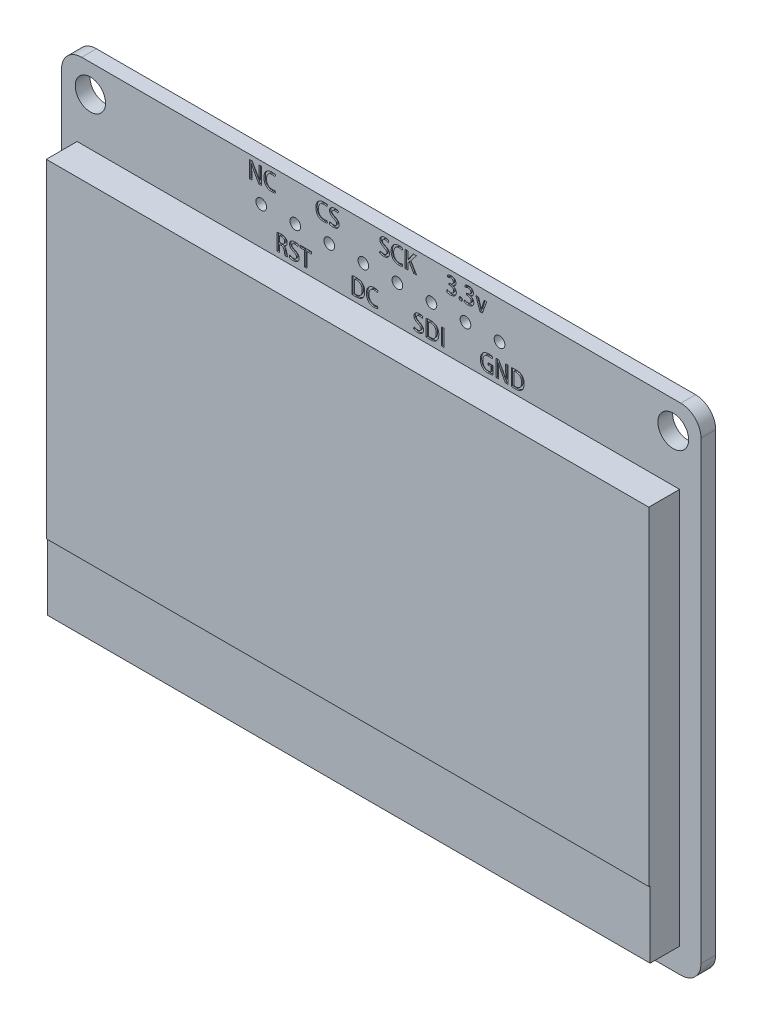
SolidWorks part; units mm, degrees
material "Plastique personnalisé"
ref_plane "Plan de face" through (0, 0, 0) normal (0, 0, 1) x (1, 0, 0)
ref_plane "Plan de dessus" through (0, 0, 0) normal (0, 1, 0) x (1, 0, 0)
ref_plane "Plan de droite" through (0, 0, 0) normal (1, 0, 0) x (0, 0, -1)
sketch "Esquisse1" plane through (0, 0, 0) normal (0, 0, 1) x (1, 0, 0)
  line L0 (4.6185, 246.0736) -> (52.2185, 246.0407) construction
  line L1 (40.983, 251.6357) -> (-0.5951, 251.6357) construction
  line L2 (4.5636, 236.0453) -> (4.5636, 254.0238) construction
  line L3 (29.8632, 214.6715) -> (54.4236, 214.6715) construction
  line L4 (52.2699, 246.817) -> (52.2699, 211.8527) construction
  line L6 (6.0636, 251.6357) -> (50.7699, 251.6357)
  line L7 (4.5636, 250.1357) -> (4.5636, 216.1715)
  line L8 (6.0636, 214.6715) -> (50.7699, 214.6715)
  line L9 (52.2699, 250.1357) -> (52.2699, 216.1715)
  arc A0 (4.5636, 216.1715) -> (6.0636, 214.6715) centre (6.0636, 216.1715) ccw
  arc A1 (6.0636, 251.6357) -> (4.5636, 250.1357) centre (6.0636, 250.1357) ccw
  arc A2 (50.7699, 251.6357) -> (52.2699, 250.1357) centre (50.7699, 250.1357) cw
  arc A3 (50.7699, 214.6715) -> (52.2699, 216.1715) centre (50.7699, 216.1715) ccw
  circle A12 centre (6.7151, 249.5559) radius 1.1307
  circle A13 centre (50.2028, 249.5609) radius 1.1474
  circle A14 centre (19.4616, 248.8369) radius 0.3977
  circle A15 centre (22.0016, 248.8369) radius 0.3977
  circle A16 centre (24.5416, 248.8369) radius 0.3977
  circle A17 centre (27.0816, 248.8369) radius 0.3977
  circle A18 centre (29.6216, 248.8369) radius 0.3977
  circle A19 centre (32.1616, 248.8369) radius 0.3977
  circle A20 centre (34.7016, 248.8369) radius 0.3977
  circle A21 centre (37.2416, 248.8369) radius 0.3977
  point P18 (4.5636, 251.6357)
  point P23 (52.2699, 214.6715)
  dimension "D2" = 1.5
  dimension "D1" = 47.6
  dimension "D4" = 8
sketch "active" plane through (0, 0, 0) normal (0, 0, 1) x (1, 0, 0)
  line L1 (5.7254, 246.0223) -> (50.6774, 246.0223)
  line L2 (5.7254, 246.0223) -> (5.7254, 216.504)
  line L3 (5.7254, 216.504) -> (50.6774, 216.504)
  line L4 (50.6774, 246.0223) -> (50.6774, 216.504)
extrude "Boss.-Extru.1" add sketch "Esquisse1" along normal blind 1.1
extrude "Boss.-Extru.2" add sketch "active" along normal blind 3.4
sketch "Esquisse3" plane through (0, 0, 3.4) normal (0, 0, 1) x (1, 0, 0)
  line L0 (50.6774, 246.0223) -> (50.6774, 216.504) construction
  line L1 (5.7254, 216.504) -> (50.6774, 216.504)
  line L2 (5.7254, 216.504) -> (5.7254, 221.5072)
  line L3 (5.7254, 221.5072) -> (50.6774, 221.5072)
  line L4 (50.6774, 216.504) -> (50.6774, 221.5072)
extrude "Enlèv. mat.-Extru.1" cut sketch "Esquisse3" against normal blind 0.1
sketch "Esquisse4" plane through (0, 0, 1.1) normal (0, 0, 1) x (1, 0, 0)
  text T0 "OPEN-SMART" font "@Adobe Heiti Std R" height in points 4
extrude "Enlèv. mat.-Extru.2" cut sketch "Esquisse4" against normal blind 0.1
sketch "Esquisse5" plane through (0, 0, 1.1) normal (0, 0, 1) x (1, 0, 0)
  text T0 "NC        CS        SCK      3.3v" font "@Adobe Heiti Std R" height in points 4
extrude "Enlèv. mat.-Extru.3" cut sketch "Esquisse5" against normal blind 0.1
sketch "Esquisse6" plane through (0, 0, 1.1) normal (0, 0, 1) x (1, 0, 0)
  text T0 "RST        DC       SDI       GND" font "@Adobe Heiti Std R" height in points 4
extrude "Enlèv. mat.-Extru.4" cut sketch "Esquisse6" against normal blind 0.1
